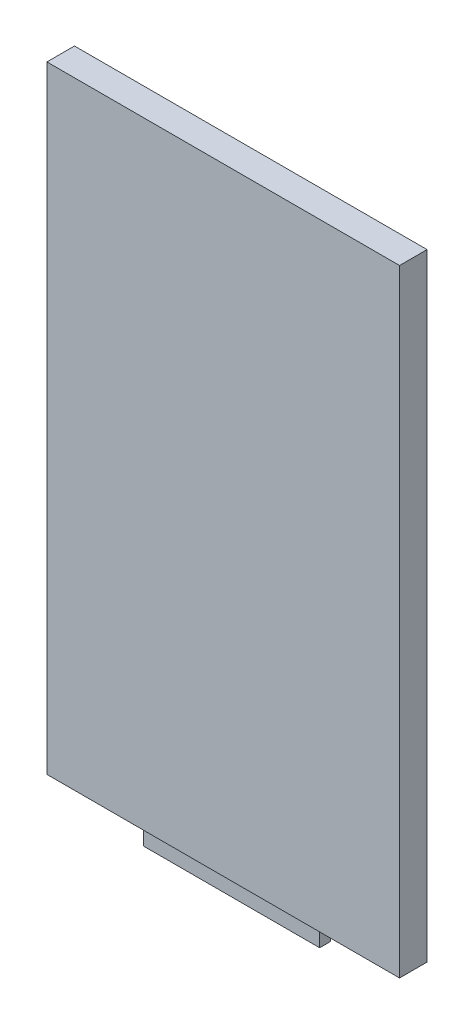
SolidWorks part; units mm, degrees
ref_plane "Front Plane" through (0, 0, 0) normal (0, 0, 1) x (1, 0, 0)
ref_plane "Top Plane" through (0, 0, 0) normal (0, 1, 0) x (1, 0, 0)
ref_plane "Right Plane" through (0, 0, 0) normal (1, 0, 0) x (0, 0, -1)
sketch "Sketch2" plane through (0, 0, 0) normal (0, 1, 0) x (1, 0, 0)
  line L1 (16, -1.25) -> (-16, -1.25)
  line L2 (16, -1.25) -> (16, 1.25)
  line L3 (16, 1.25) -> (-16, 1.25)
  line L4 (-16, -1.25) -> (-16, 1.25)
  line L5 (16, -1.25) -> (-16, 1.25) construction
  line L6 (16, 1.25) -> (-16, -1.25) construction
  point P0 (0, 0)
  dimension "D1" = 32
  dimension "D2" = 2.5
extrude "Boss-Extrude1" add sketch "Sketch2" along normal blind 56
sketch "Sketch4" plane through (0, 0, 0) normal (0, -1, 0) x (1, 0, 0)
  line L0 (16, -1.25) -> (-16, -1.25) construction
  line L1 (-8, 0.5) -> (8, 0.5)
  line L2 (-8, 0.5) -> (-8, -0.5)
  line L3 (-8, -0.5) -> (8, -0.5)
  line L4 (8, 0.5) -> (8, -0.5)
  line L5 (-8, 0.5) -> (8, -0.5) construction
  line L6 (-8, -0.5) -> (8, 0.5) construction
  point P0 (0, 0)
  dimension "D1" = 1
  dimension "D2" = 16
  dimension "D3" = 0.75
extrude "Boss-Extrude2" add sketch "Sketch4" along normal blind 2
